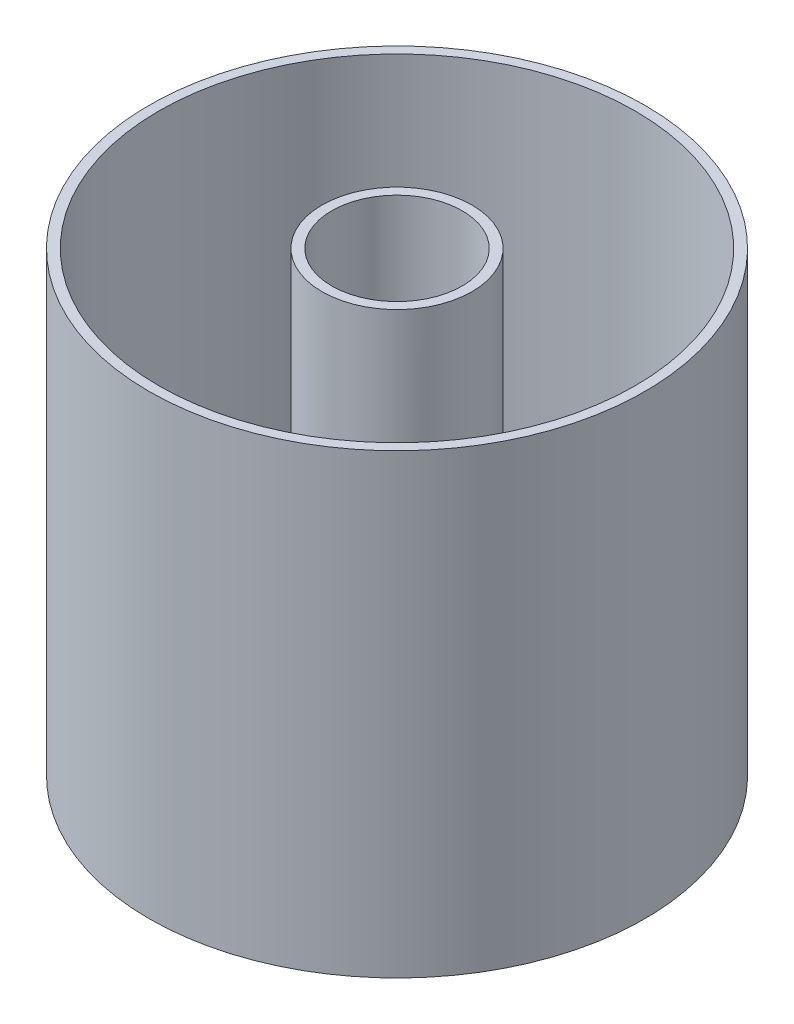
SolidWorks part; units mm, degrees
ref_plane "Front Plane" through (0, 0, 0) normal (0, 0, 1) x (1, 0, 0)
ref_plane "Top Plane" through (0, 0, 0) normal (0, 1, 0) x (1, 0, 0)
ref_plane "Right Plane" through (0, 0, 0) normal (1, 0, 0) x (0, 0, -1)
sketch "Sketch1" plane through (0, 0, 0) normal (0, 1, 0) x (1, 0, 0)
  circle A0 centre (0, 0) radius 76
  circle A1 centre (0, 0) radius 20
  circle A2 centre (0, 0) radius 73
  circle A3 centre (0, 0) radius 23
  dimension "D1" = 152
  dimension "D2" = 40
  dimension "D3" = 3
  dimension "D4" = 3
extrude "Boss-Extrude3" add sketch "Sketch1" along normal blind 135 contours A0 A2 | A3 A1
sketch "Sketch2" plane through (0, 0, 0) normal (0, -1, 0) x (1, 0, 0)
  circle A0 centre (0, 0) radius 76
extrude "Boss-Extrude4" add sketch "Sketch2" along normal blind 5
